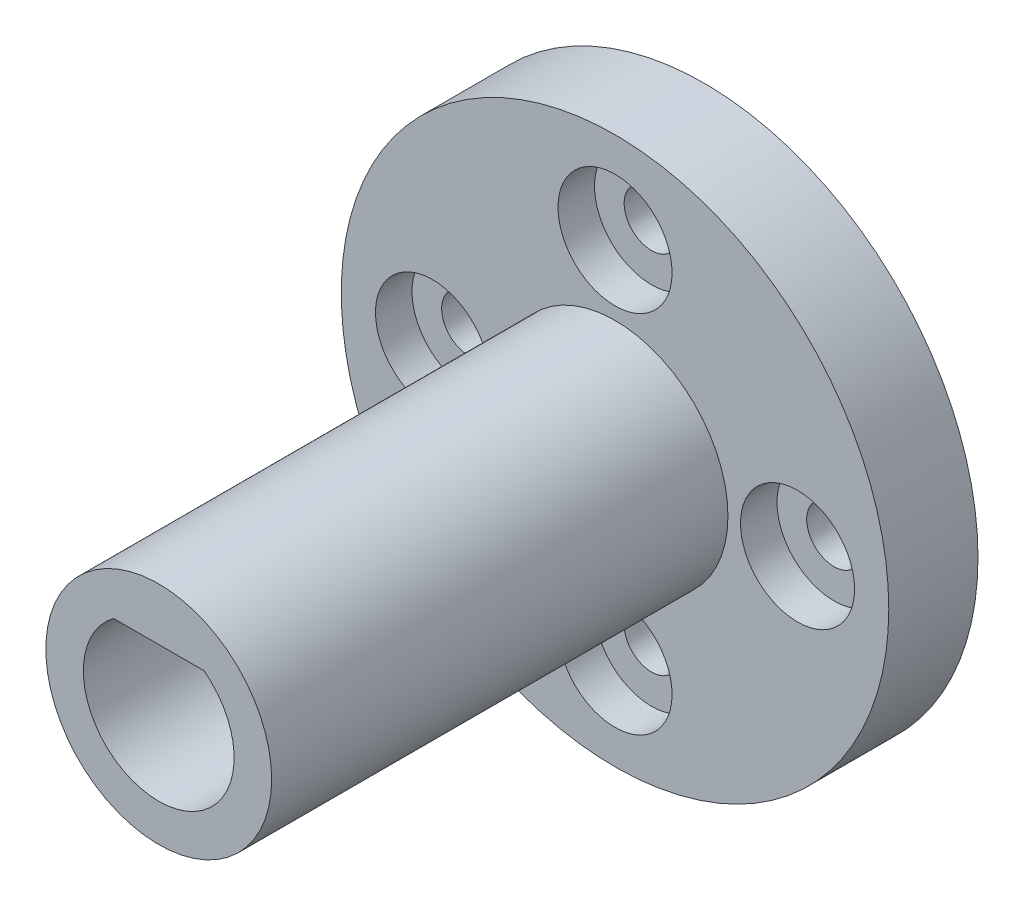
SolidWorks part; units mm, degrees
ref_plane "Plan de face" through (0, 0, 0) normal (0, 0, 1) x (1, 0, 0)
ref_plane "Plan de dessus" through (0, 0, 0) normal (0, 1, 0) x (1, 0, 0)
ref_plane "Plan de droite" through (0, 0, 0) normal (1, 0, 0) x (0, 0, -1)
sketch "Esquisse1" plane through (0, 0, 0) normal (0, 0, 1) x (1, 0, 0)
  circle A0 centre (0, 0) radius 12
  dimension "D1" = 24
extrude "Boss.-Extru.1" add sketch "Esquisse1" along normal blind 3.91
sketch "Esquisse6" plane through (0, 0, 0) normal (0, 0, -1) x (-1, 0, 0)
  circle A0 centre (0, 0) radius 4
  dimension "D1" = 8
extrude "Enlèv. mat.-Extru.2" cut sketch "Esquisse6" against normal blind 1.91
sketch "Esquisse7" plane through (0, 0, 3.91) normal (0, 0, 1) x (1, 0, 0)
  line L0 (1.9817, 2.645) -> (-1.9817, 2.645)
  line L1 (-5.4714, -3.305) -> (6.192, -3.305) construction
  arc A0 (-1.9817, 2.645) -> (1.9817, 2.645) centre (0, 0) ccw
  circle A1 centre (0, 0) radius 4.95
  dimension "D1" = 6.61
  dimension "D3" = 9.9
  dimension "D2" = 5.95
extrude "Boss.-Extru.2" add sketch "Esquisse7" along normal blind 20 contours A1 L1 A0 L0 | L1 A1
hole_wizard "Chambrage pour vis à tête ronde bombée M21" positions "Esquisse10" profile "Esquisse11" counterbore size "M2" standard "Ansi Metric" end condition through all
sketch "Esquisse10" plane through (0, 0, 3.91) normal (0, 0, 1) x (1, 0, 0)
  point P0 (0, 8)
  dimension "D1" = 8
sketch "Esquisse11" plane through (0, 8, 3.91) normal (1, 0, 0) x (0, -1, 0)
  line L0 (0, 0) -> (0, 3.91)
  line L1 (0, 3.91) -> (1.2, 3.91)
  line L3 (1.2, 3.91) -> (1.2, 1.6)
  line L4 (1.2, 1.6) -> (2.5, 1.6)
  line L5 (2.5, 1.6) -> (2.5, 0)
  line L7 (2.5, 0) -> (0, 0)
  line L11 (0, -6.35) -> (0, 107.95) construction
  dimension "Diamètre du perçage jusqu'au prochain" = 2.4
  dimension "Profondeur du perçage jusqu'au prochain" = 3.91
  dimension "Diamètre du chambrage" = 5
  dimension "Profondeur du chambrage" = 1.6
pattern_circular "Répétition circulaire2" count 4 every 90 about axis through (0, 0, 0) along (0, 0, 1) of "Chambrage pour vis à tête ronde bombée M21"
